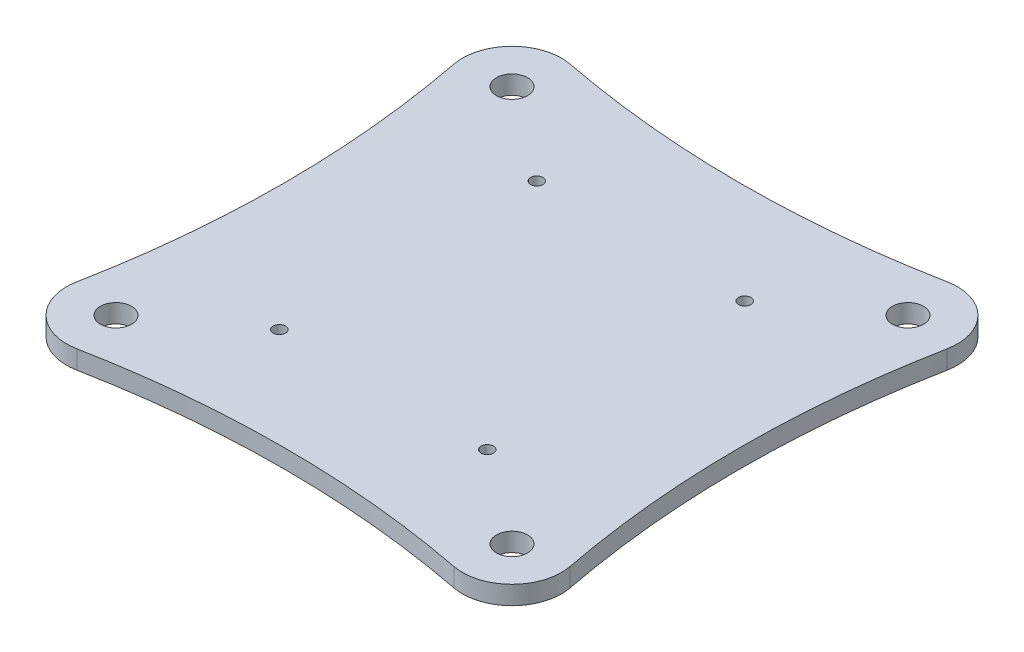
SolidWorks part; units mm, degrees
ref_plane "Front Plane" through (0, 0, 0) normal (0, 0, 1) x (1, 0, 0)
ref_plane "Top Plane" through (0, 0, 0) normal (0, 1, 0) x (1, 0, 0)
ref_plane "Right Plane" through (0, 0, 0) normal (1, 0, 0) x (0, 0, -1)
sketch "Sketch1" plane through (0, 0, 0) normal (0, 1, 0) x (1, 0, 0)
  line L4 (-50.8, 50.8) -> (50.8, -50.8) construction
  line L5 (26.67, 33.02) -> (-26.67, -33.02) construction
  arc A0 (-48.381, 63.2675) -> (-63.2675, 48.381) centre (-50.8, 50.8) ccw
  arc A1 (-63.2675, -48.381) -> (-48.381, -63.2675) centre (-50.8, -50.8) ccw
  arc A2 (48.381, -63.2675) -> (63.2675, -48.381) centre (50.8, -50.8) ccw
  arc A3 (63.2675, 48.381) -> (48.381, 63.2675) centre (50.8, 50.8) ccw
  circle A4 centre (-50.8, 50.8) radius 4
  circle A5 centre (50.8, 50.8) radius 4
  circle A6 centre (50.8, -50.8) radius 4
  circle A7 centre (-50.8, -50.8) radius 4
  circle A8 centre (-26.67, 33.02) radius 1.5875
  circle A9 centre (26.67, 33.02) radius 1.5875
  circle A10 centre (-26.67, -33.02) radius 1.5875
  circle A11 centre (26.67, -33.02) radius 1.5875
  arc A12 (-48.381, 63.2675) -> (48.381, 63.2675) centre (0, 312.6172) ccw
  arc A13 (-63.2675, 48.381) -> (-63.2675, -48.381) centre (-312.6172, 0) cw
  arc A14 (63.2675, 48.381) -> (63.2675, -48.381) centre (312.6172, 0) ccw
  arc A15 (48.381, -63.2675) -> (-48.381, -63.2675) centre (0, -312.6172) ccw
  point P16 (0, 0)
  point P26 (0, 0)
  dimension "D3" = 12.7
  dimension "D4" = 8
  dimension "D7" = 3.175
  dimension "D8" = 254
  dimension "D1" = 101.6
  dimension "D2" = 101.6
  dimension "D5" = 53.34
  dimension "D6" = 66.04
extrude "Boss-Extrude1" add sketch "Sketch1" along normal blind 4.7625
